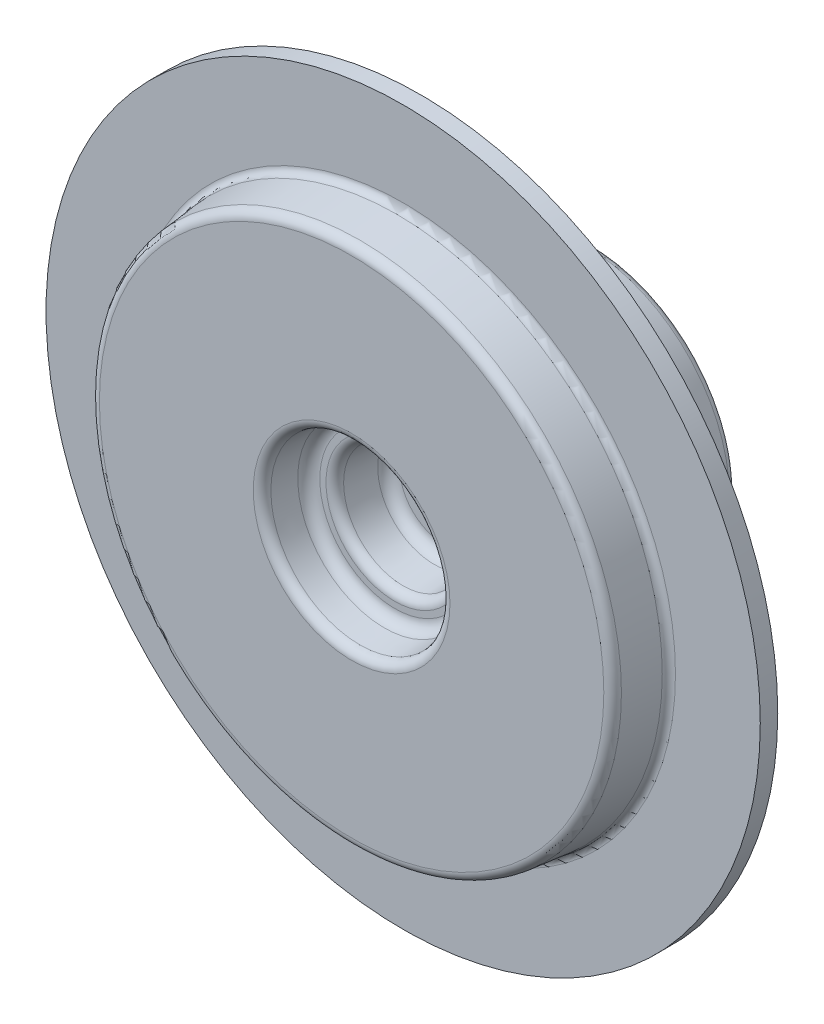
SolidWorks part; units mm, degrees
ref_plane "Front Plane" through (0, 0, 0) normal (0, 0, 1) x (1, 0, 0)
ref_plane "Top Plane" through (0, 0, 0) normal (0, 1, 0) x (1, 0, 0)
ref_plane "Right Plane" through (0, 0, 0) normal (1, 0, 0) x (0, 0, -1)
sketch "Sketch1" plane through (0, 0, 0) normal (0, 1, 0) x (1, 0, 0)
  line L0 (-1253.2569, 0) -> (61409.5859, 0) construction
  line L1 (0, -1253.2569) -> (0, 61409.5859) construction
  line L2 (26.1, 49.296) -> (36.6556, 49.296)
  line L4 (38.6, 67.796) -> (61.6, 67.796)
  line L5 (61.6, 67.796) -> (65.9905, 42.896)
  line L6 (65.9905, 42.896) -> (76.6, 42.896)
  line L8 (79.2802, 17.396) -> (111.2187, 17.396)
  line L10 (111.8, -35.404) -> (38.6, -35.404)
  line L12 (36.6556, -16.904) -> (25.8898, -16.904)
  line L14 (61.6, 67.796) -> (61.6, 17.396) construction
  line L15 (-895.9794, -11.7694) -> (49104.0206, -11.7694) construction
  line L16 (111.2187, 17.396) -> (114.1244, -10.2504)
  line L17 (114.1244, -13.2884) -> (111.8, -35.404)
  line L18 (26.1, 49.296) -> (23.653, 26.0143)
  line L19 (23.653, 26.0143) -> (0, 26.0143)
  line L20 (0, 26.0143) -> (0, 4.3777)
  line L21 (0, 4.3777) -> (23.653, 4.3777)
  line L22 (23.653, 4.3777) -> (25.8898, -16.904)
  line L23 (-973.9, 15.196) -> (49026.1, 15.196) construction
  line L24 (26.1, 49.296) -> (26.1, 58.7687) construction
  line L25 (111.2187, 17.396) -> (111.2187, 35.1399) construction
  line L26 (76.6, 42.896) -> (79.2802, 17.396)
  line L27 (38.6, 67.796) -> (36.6556, 49.296)
  line L28 (38.6, -35.404) -> (36.6556, -16.904)
  line L29 (114.1244, -10.2504) -> (127.7944, -10.2504)
  line L30 (127.7944, -10.2504) -> (144.3107, -5.7945)
  line L31 (144.3107, -5.7945) -> (153.2059, -5.7945)
  line L32 (153.2059, -5.7945) -> (153.2059, -13.2884)
  line L33 (153.2059, -13.2884) -> (114.1244, -13.2884)
  point P12 (95.2494, 17.396)
  point P16 (153.2059, -5.7945)
  point P21 (0, 0)
  dimension "D1" = 111.8
  dimension "D2" = 38.6
  dimension "D3" = 38.6
  dimension "D4" = 26.1
  dimension "D5" = 61.6
  dimension "D6" = 76.6
  dimension "D7" = 103.2
  dimension "D8" = 52.8
  dimension "D9" = 25.5
  dimension "D10" = 10
  dimension "D11" = 18.5
  dimension "D12" = 18.5
  dimension "D13" = 6
  dimension "D14" = 6
  dimension "D15" = 6
  dimension "D16" = 6
  dimension "D17" = 6
  dimension "D18" = 6
  dimension "D19" = 3.038
  dimension "D20" = 1.519
  dimension "D21" = 13.67
  dimension "D22" = 114.1244
revolve "Revolve1" add sketch "Sketch1" angle 360 about L1
fillet "Fillet1" radius 4 1 edges at (61.6, 0, -67.796)
fillet "Fillet2" radius 4 6 edges at (25.8898, 0, 16.904) (26.1, 0, -49.296) (111.8, 0, 35.404) (111.2187, 0, -17.396) (76.6, 0, -42.896) (38.6, 0, -67.796)
fillet "Fillet3" radius 4 1 edges at (38.6, 0, 35.404)
fillet "Fillet4" radius 5 6 edges at (36.6556, 0, 16.904) (23.653, 0, -4.3777) (79.2802, 0, -17.396) (65.9905, 0, -42.896) (36.6556, 0, -49.296) (23.653, 0, -26.0143)
fillet "Fillet5" radius 3 2 edges at (114.1244, 0, 13.2884) (114.1244, 0, 10.2504)
